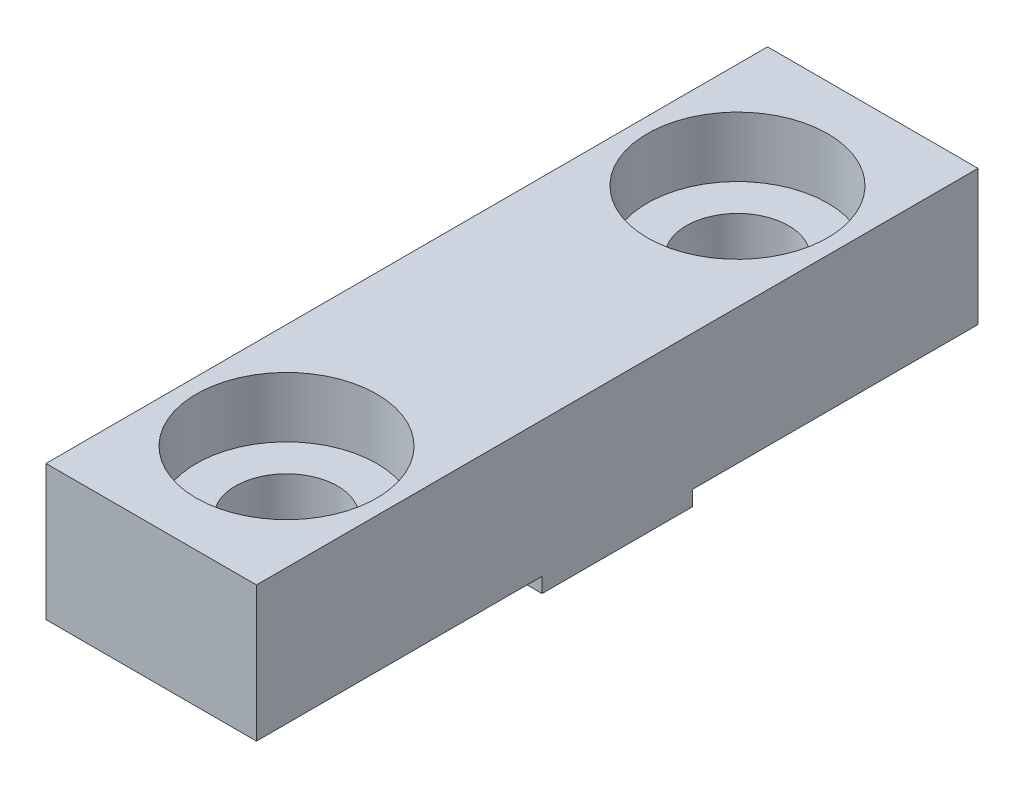
SolidWorks part; units mm, degrees
ref_plane "Front Plane" through (0, 0, 0) normal (0, 0, 1) x (1, 0, 0)
ref_plane "Top Plane" through (0, 0, 0) normal (0, 1, 0) x (1, 0, 0)
ref_plane "Right Plane" through (0, 0, 0) normal (1, 0, 0) x (0, 0, -1)
ref_plane "Plane1" through (0, 6, 0) normal (0, 1, 0) x (1, 0, 0)
sketch "Sketch1" plane through (0, 6, 0) normal (0, 1, 0) x (1, 0, 0)
  line L0 (-55, 12) -> (-48, 12)
  line L1 (-48, 12) -> (-48, -12)
  line L2 (-48, -12) -> (-55, -12)
  line L3 (-55, -12) -> (-55, 12)
extrude "Boss-Extrude1" add sketch "Sketch1" along normal blind 4.5
sketch "Sketch2" plane through (0, 6, 0) normal (0, 1, 0) x (1, 0, 0)
  line L0 (-55, 2.5) -> (-48, 2.5)
  line L1 (-48, 2.5) -> (-48, -2.5)
  line L2 (-48, -2.5) -> (-55, -2.5)
  line L3 (-55, -2.5) -> (-55, 2.5)
extrude "Boss-Extrude2" add sketch "Sketch2" against normal blind 0.5
ref_plane "Plane2" through (0, 10.5, 0) normal (0, 1, 0) x (1, 0, 0)
sketch "Sketch3" plane through (0, 10.5, 0) normal (0, 1, 0) x (1, 0, 0)
  circle A0 centre (-51.5, 7.5) radius 1.7
  circle A1 centre (-51.5, -7.5) radius 1.7
extrude "Cut-Extrude1" cut sketch "Sketch3" against normal through all
sketch "Sketch4" plane through (0, 10.5, 0) normal (0, 1, 0) x (1, 0, 0)
  circle A0 centre (-51.5, 7.5) radius 3
  circle A1 centre (-51.5, -7.5) radius 3
extrude "Cut-Extrude2" cut sketch "Sketch4" against normal blind 2
